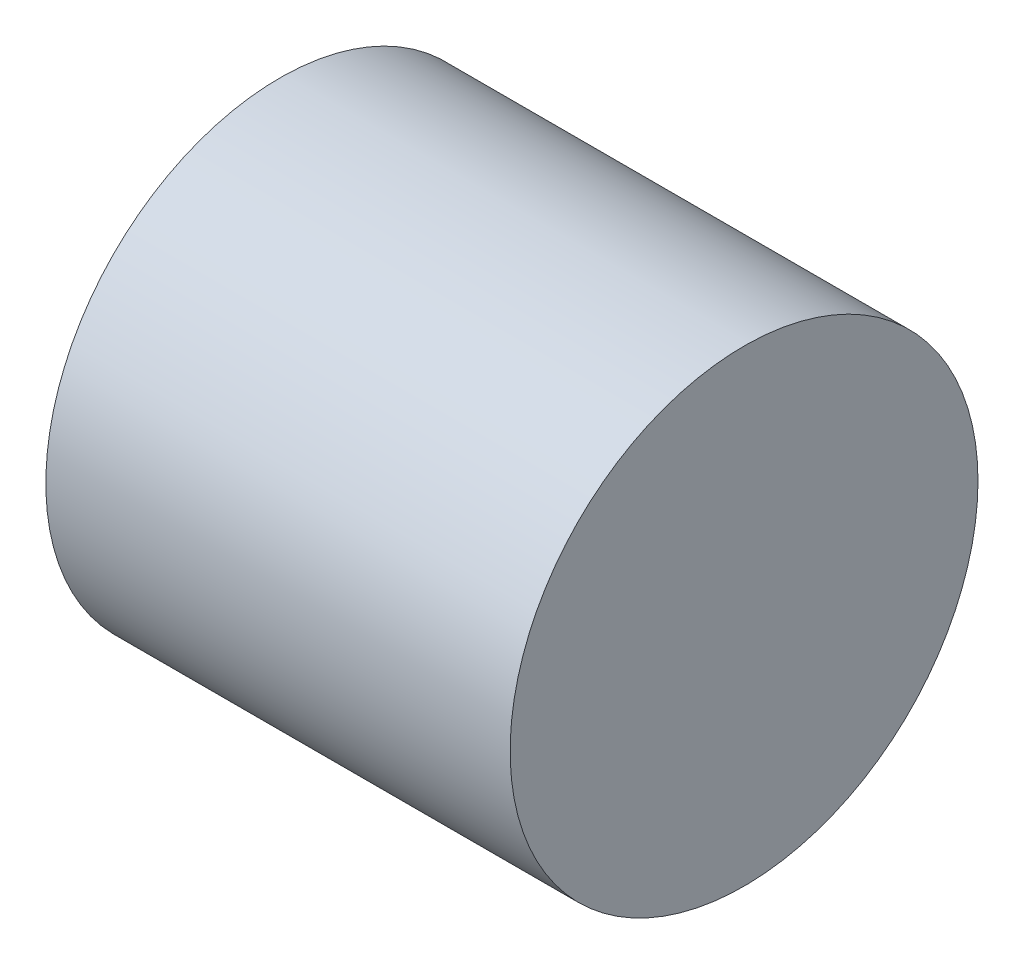
SolidWorks part; units mm, degrees
ref_plane "Front Plane" through (0, 0, 0) normal (0, 0, 1) x (1, 0, 0)
ref_plane "Top Plane" through (0, 0, 0) normal (0, 1, 0) x (1, 0, 0)
ref_plane "Right Plane" through (0, 0, 0) normal (1, 0, 0) x (0, 0, -1)
sketch "Sketch1" plane through (0, 0, 0) normal (1, 0, 0) x (0, 0, -1)
  circle A0 centre (-7.978, 45.8221) radius 5.1191
extrude "Boss-Extrude1" add sketch "Sketch1" along normal blind 10.16
